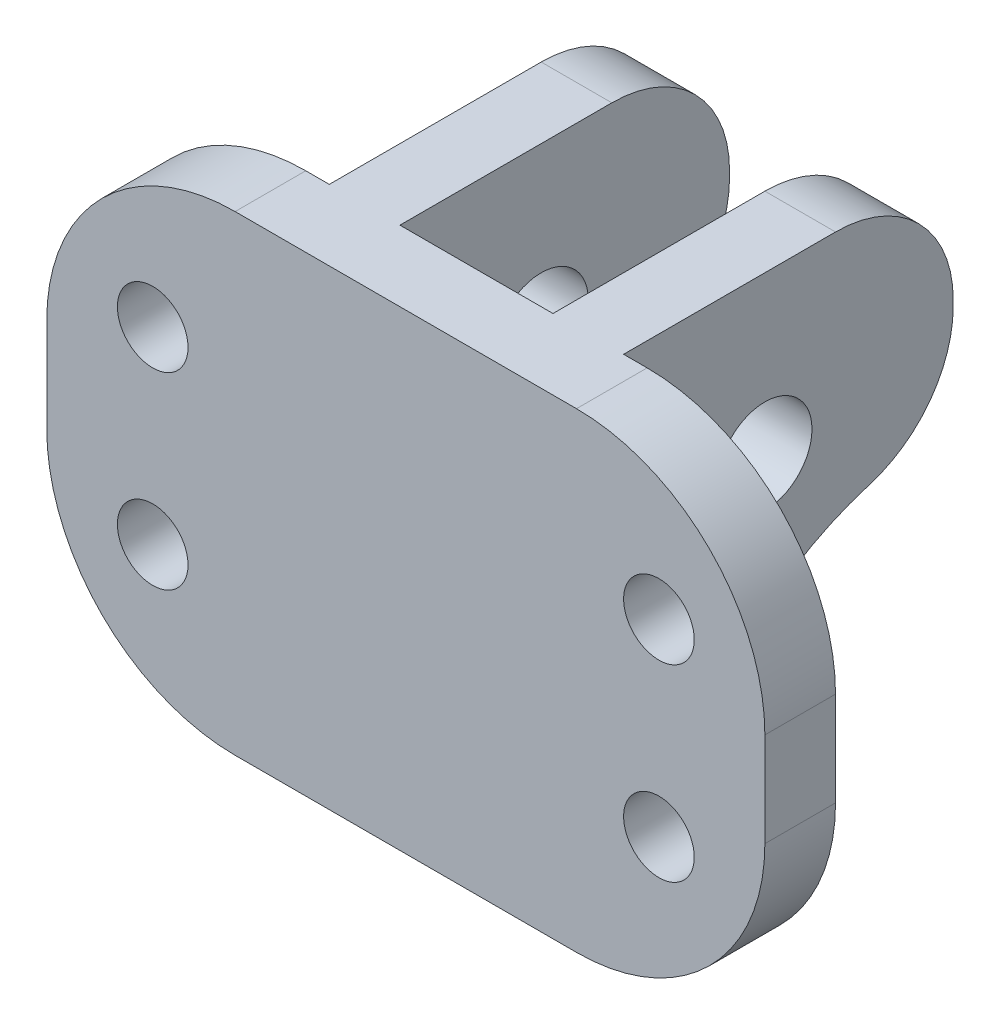
SolidWorks part; units mm, degrees
material "6061 合金"
ref_plane "前视基准面" through (0, 0, 0) normal (0, 0, 1) x (1, 0, 0)
ref_plane "上视基准面" through (0, 0, 0) normal (0, 1, 0) x (1, 0, 0)
ref_plane "右视基准面" through (0, 0, 0) normal (1, 0, 0) x (0, 0, -1)
sketch "草图1" plane through (0, 0, 0) normal (0, 1, 0) x (1, 0, 0)
  line L1 (-6.25, -8.5) -> (6.25, -8.5)
  line L2 (-6.25, -8.5) -> (-6.25, 8.5)
  line L3 (-6.25, 8.5) -> (6.25, 8.5)
  line L4 (6.25, -8.5) -> (6.25, 8.5)
  line L5 (-6.25, -8.5) -> (6.25, 8.5) construction
  line L6 (-6.25, 8.5) -> (6.25, -8.5) construction
  line L7 (-3.25, 8.5) -> (3.25, 8.5)
  line L8 (-3.25, 8.5) -> (-3.25, -5.5)
  line L9 (-3.25, -5.5) -> (3.25, -5.5)
  line L10 (3.25, 8.5) -> (3.25, -5.5)
  point P0 (0, 0)
  dimension "D1" = 12.5
  dimension "D2" = 17
  dimension "D3" = 3
  dimension "D4" = 3
  dimension "D5" = 3
extrude "凸台-拉伸1" add sketch "草图1" along normal blind 27 contours L3 L10 L9 L8 L2 L1 L4
sketch "草图3" plane through (6.25, 0, 0) normal (1, 0, 0) x (0, 0, -1)
  line L0 (-5.5, 13.5) -> (8.5, 13.5) construction
  line L1 (-5.5, 27) -> (-5.5, 0) construction
  line L2 (8.5, 27) -> (8.5, 0) construction
  line L3 (-8.5, 27) -> (8.5, 27) construction
  circle A1 centre (0.5, 20.25) radius 2
  dimension "D4" = 8
  dimension "D5" = 6.75
extrude "切除-拉伸2" cut sketch "草图3" against normal through all
fillet "圆角1" radius 5 4 edges at (-4.75, 27, -8.5) (-4.75, 0, -8.5) (4.75, 0, -8.5) (4.75, 27, -8.5)
sketch "草图4" plane through (0, 0, 8.5) normal (0, 0, 1) x (1, 0, 0)
  line L1 (-6.25, 0) -> (-15.25, 0)
  line L2 (-6.25, 0) -> (-6.25, 27)
  line L3 (-6.25, 27) -> (-15.25, 27)
  line L4 (-15.25, 0) -> (-15.25, 27)
  line L5 (6.25, 0) -> (15.25, 0)
  line L6 (6.25, 0) -> (6.25, 27)
  line L7 (6.25, 27) -> (15.25, 27)
  line L8 (15.25, 0) -> (15.25, 27)
  circle A0 centre (10.75, 13) radius 1.5
  circle A1 centre (10.75, 21) radius 1.5
  circle A2 centre (-10.75, 13) radius 1.5
  circle A3 centre (-10.75, 21) radius 1.5
  dimension "D5" = 3
  dimension "D6" = 3
  dimension "D7" = 3
  dimension "D8" = 3
  dimension "D9" = 13
  dimension "D10" = 8
  dimension "D11" = 8
  dimension "D12" = 13
  dimension "D13" = 4.5
  dimension "D14" = 4.5
  dimension "D15" = 4.5
  dimension "D16" = 4.5
  dimension "D1" = 27
  dimension "D2" = 9
  dimension "D3" = 27
  dimension "D4" = 9
extrude "凸台-拉伸2" add sketch "草图4" against normal blind 3
fillet "圆角2" radius 8 2 edges at (15.25, 27, 7) (-15.25, 27, 7)
sketch "草图5" plane through (0, 0, 8.5) normal (0, 0, 1) x (1, 0, 0)
  line L1 (-19.3327, 7) -> (19.3327, 7)
  line L2 (-19.3327, 7) -> (-19.3327, -7)
  line L3 (-19.3327, -7) -> (19.3327, -7)
  line L4 (19.3327, 7) -> (19.3327, -7)
  line L5 (-19.3327, 7) -> (19.3327, -7) construction
  line L6 (-19.3327, -7) -> (19.3327, 7) construction
  point P0 (0, 0)
  dimension "D1" = 14
extrude "切除-拉伸3" cut sketch "草图5" against normal through all
fillet "圆角3" radius 5 2 edges at (-4.75, 7, -8.5) (4.75, 7, -8.5)
fillet "圆角4" radius 8 2 edges at (-15.25, 7, 7) (15.25, 7, 7)
sketch "草图6" plane through (6.25, 0, 0) normal (1, 0, 0) x (0, 0, -1)
  circle A0 centre (8.5, 5) radius 12.5
  dimension "D1" = 25
extrude "切除-拉伸5" cut sketch "草图6" against normal through all
fillet "圆角5" radius 5 2 edges at (-4.75, 17.5, -8.5) (4.75, 17.5, -8.5)
